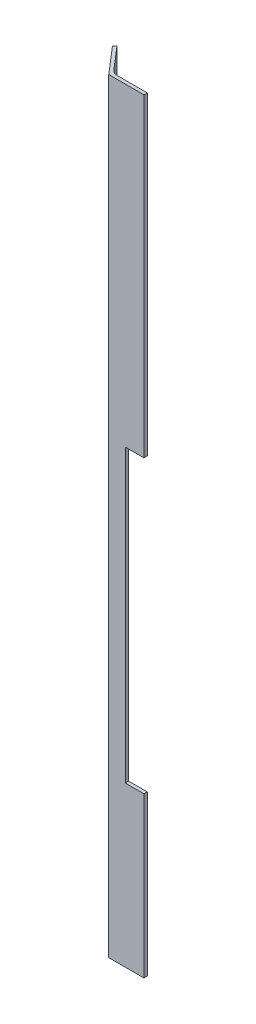
SolidWorks part; units mm, degrees
ref_plane "Спереди" through (0, 0, 0) normal (0, 0, 1) x (1, 0, 0)
ref_plane "Сверху" through (0, 0, 0) normal (0, 1, 0) x (1, 0, 0)
ref_plane "Справа" through (0, 0, 0) normal (1, 0, 0) x (0, 0, -1)
sketch "Эскиз1" plane through (0, 0, 0) normal (0, 1, 0) x (1, 0, 0)
  line L0 (-17.7667, 14.446) -> (-16.3084, 15.7)
  line L1 (-0.9318, 0.4869) -> (17.1228, 0.4869)
  line L2 (-16.3084, 15.7) -> (-4.7229, 2.2269)
  line L3 (-17.7667, 14.446) -> (-4.0435, -1.5131)
  line L4 (-4.0435, -1.5131) -> (17.1228, -1.5131)
  line L5 (17.1228, -1.5131) -> (17.1228, 0.4869)
  arc A0 (-0.9318, 0.4869) -> (-4.7229, 2.2269) centre (-0.9318, 5.4869) cw
  dimension "D1" = 5
extrude "Вытянуть1" add sketch "Эскиз1" along normal blind 460 from offset 40
sketch "Эскиз2" plane through (0, 0, 1.5131) normal (0, 0, 1) x (1, 0, 0)
  line L1 (19.8228, 310.9032) -> (5.9287, 310.9032)
  line L2 (19.8228, 310.9032) -> (19.8228, 135.9413)
  line L3 (19.8228, 135.9413) -> (5.9287, 135.9413)
  line L4 (5.9287, 310.9032) -> (5.9287, 135.9413)
extrude "Вырез-Вытянуть1" cut sketch "Эскиз2" against normal through all
